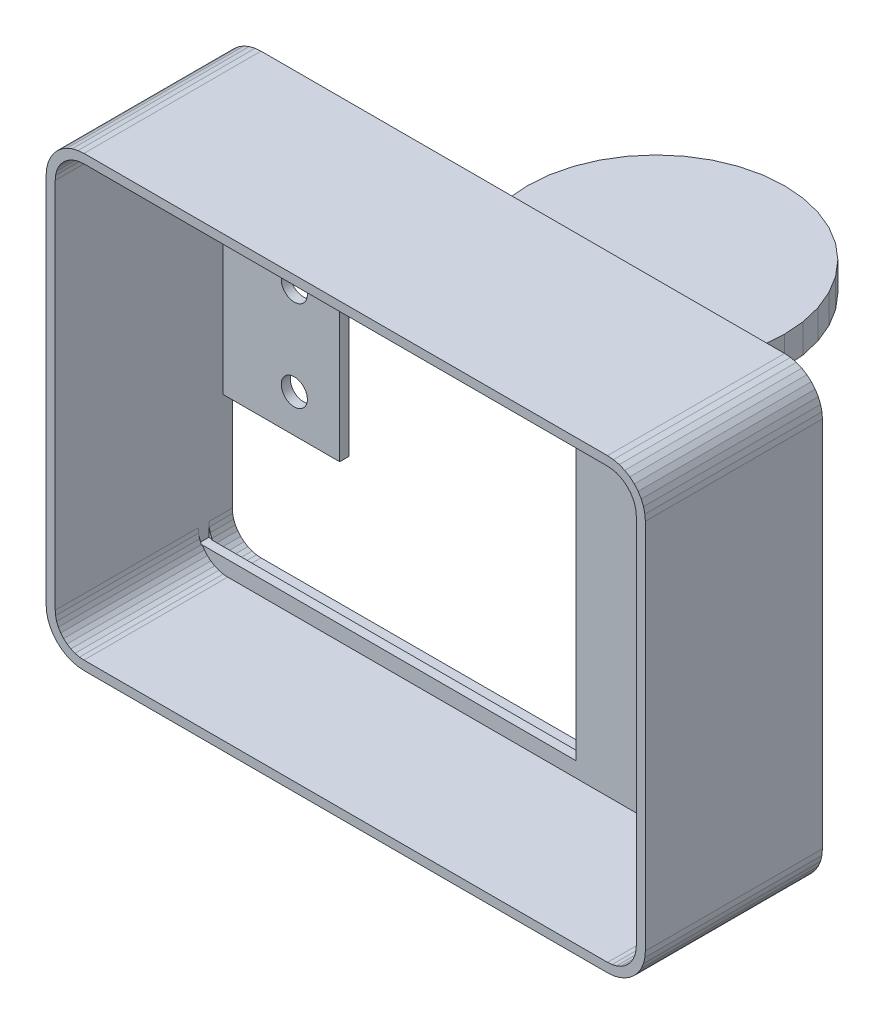
SolidWorks part; units mm, degrees
ref_plane "Front Plane" through (0, 0, 0) normal (0, 0, 1) x (1, 0, 0)
ref_plane "Top Plane" through (0, 0, 0) normal (0, 1, 0) x (1, 0, 0)
ref_plane "Right Plane" through (0, 0, 0) normal (1, 0, 0) x (0, 0, -1)
sketch "Sketch1" plane through (0, 0, 0) normal (0, 0, 1) x (1, 0, 0)
  line L0 (-41.6, -24.6) -> (-41.5384, -25.3822)
  line L1 (-41.5384, -25.3822) -> (-41.3553, -26.1451)
  line L2 (-41.3553, -26.1451) -> (-41.055, -26.87)
  line L3 (-41.055, -26.87) -> (-40.6451, -27.5389)
  line L4 (-40.6451, -27.5389) -> (-40.1355, -28.1355)
  line L5 (-40.1355, -28.1355) -> (-39.5389, -28.6451)
  line L6 (-39.5389, -28.6451) -> (-38.87, -29.055)
  line L7 (-38.87, -29.055) -> (-38.1451, -29.3553)
  line L8 (-38.1451, -29.3553) -> (-37.3822, -29.5384)
  line L9 (-37.3822, -29.5384) -> (-36.6, -29.6)
  line L10 (-36.6, -29.6) -> (32.6, -29.6)
  line L11 (32.6, -29.6) -> (33.3822, -29.5384)
  line L12 (33.3822, -29.5384) -> (34.1451, -29.3553)
  line L13 (34.1451, -29.3553) -> (34.87, -29.055)
  line L14 (34.87, -29.055) -> (35.5389, -28.6451)
  line L15 (35.5389, -28.6451) -> (36.1355, -28.1355)
  line L16 (36.1355, -28.1355) -> (36.6451, -27.5389)
  line L17 (36.6451, -27.5389) -> (37.055, -26.87)
  line L18 (37.055, -26.87) -> (37.3553, -26.1451)
  line L19 (37.3553, -26.1451) -> (37.5384, -25.3822)
  line L20 (37.5384, -25.3822) -> (37.6, -24.6)
  line L21 (37.6, -24.6) -> (37.6, 24.6)
  line L22 (37.6, 24.6) -> (37.5384, 25.3822)
  line L23 (37.5384, 25.3822) -> (37.3553, 26.1451)
  line L24 (37.3553, 26.1451) -> (37.055, 26.87)
  line L25 (37.055, 26.87) -> (36.6451, 27.5389)
  line L26 (36.6451, 27.5389) -> (36.1355, 28.1355)
  line L27 (36.1355, 28.1355) -> (35.5389, 28.6451)
  line L28 (35.5389, 28.6451) -> (34.87, 29.055)
  line L29 (34.87, 29.055) -> (34.1451, 29.3553)
  line L30 (34.1451, 29.3553) -> (33.3822, 29.5384)
  line L31 (33.3822, 29.5384) -> (32.6, 29.6)
  line L32 (32.6, 29.6) -> (-36.6, 29.6)
  line L33 (-36.6, 29.6) -> (-37.3822, 29.5384)
  line L34 (-37.3822, 29.5384) -> (-38.1451, 29.3553)
  line L35 (-38.1451, 29.3553) -> (-38.87, 29.055)
  line L36 (-38.87, 29.055) -> (-39.5389, 28.6451)
  line L37 (-39.5389, 28.6451) -> (-40.1355, 28.1355)
  line L38 (-40.1355, 28.1355) -> (-40.6451, 27.5389)
  line L39 (-40.6451, 27.5389) -> (-41.055, 26.87)
  line L40 (-41.055, 26.87) -> (-41.3553, 26.1451)
  line L41 (-41.3553, 26.1451) -> (-41.5384, 25.3822)
  line L42 (-41.5384, 25.3822) -> (-41.6, 24.6)
  line L43 (-41.6, 24.6) -> (-41.6, -24.6)
extrude "Boss-Extrude1" add sketch "Sketch1" along normal blind 23.4 from offset 23.4
sketch "Sketch2" plane through (0, 0, 0) normal (0, 0, 1) x (1, 0, 0)
  line L0 (-40.4, -24.6) -> (-40.3532, -25.1945)
  line L1 (-40.3532, -25.1945) -> (-40.214, -25.7743)
  line L2 (-40.214, -25.7743) -> (-39.9858, -26.3252)
  line L3 (-39.9858, -26.3252) -> (-39.6743, -26.8336)
  line L4 (-39.6743, -26.8336) -> (-39.287, -27.287)
  line L5 (-39.287, -27.287) -> (-38.8336, -27.6743)
  line L6 (-38.8336, -27.6743) -> (-38.3252, -27.9858)
  line L7 (-38.3252, -27.9858) -> (-37.7743, -28.214)
  line L8 (-37.7743, -28.214) -> (-37.1945, -28.3532)
  line L9 (-37.1945, -28.3532) -> (-36.6, -28.4)
  line L10 (-36.6, -28.4) -> (32.6, -28.4)
  line L11 (32.6, -28.4) -> (33.1945, -28.3532)
  line L12 (33.1945, -28.3532) -> (33.7743, -28.214)
  line L13 (33.7743, -28.214) -> (34.3252, -27.9858)
  line L14 (34.3252, -27.9858) -> (34.8336, -27.6743)
  line L15 (34.8336, -27.6743) -> (35.287, -27.287)
  line L16 (35.287, -27.287) -> (35.6743, -26.8336)
  line L17 (35.6743, -26.8336) -> (35.9858, -26.3252)
  line L18 (35.9858, -26.3252) -> (36.214, -25.7743)
  line L19 (36.214, -25.7743) -> (36.3532, -25.1945)
  line L20 (36.3532, -25.1945) -> (36.4, -24.6)
  line L21 (36.4, -24.6) -> (36.4, 24.6)
  line L22 (36.4, 24.6) -> (36.3532, 25.1945)
  line L23 (36.3532, 25.1945) -> (36.214, 25.7743)
  line L24 (36.214, 25.7743) -> (35.9858, 26.3252)
  line L25 (35.9858, 26.3252) -> (35.6743, 26.8336)
  line L26 (35.6743, 26.8336) -> (35.287, 27.287)
  line L27 (35.287, 27.287) -> (34.8336, 27.6743)
  line L28 (34.8336, 27.6743) -> (34.3252, 27.9858)
  line L29 (34.3252, 27.9858) -> (33.7743, 28.214)
  line L30 (33.7743, 28.214) -> (33.1945, 28.3532)
  line L31 (33.1945, 28.3532) -> (32.6, 28.4)
  line L32 (32.6, 28.4) -> (-36.6, 28.4)
  line L33 (-36.6, 28.4) -> (-37.1945, 28.3532)
  line L34 (-37.1945, 28.3532) -> (-37.7743, 28.214)
  line L35 (-37.7743, 28.214) -> (-38.3252, 27.9858)
  line L36 (-38.3252, 27.9858) -> (-38.8336, 27.6743)
  line L37 (-38.8336, 27.6743) -> (-39.287, 27.287)
  line L38 (-39.287, 27.287) -> (-39.6743, 26.8336)
  line L39 (-39.6743, 26.8336) -> (-39.9858, 26.3252)
  line L40 (-39.9858, 26.3252) -> (-40.214, 25.7743)
  line L41 (-40.214, 25.7743) -> (-40.3532, 25.1945)
  line L42 (-40.3532, 25.1945) -> (-40.4, 24.6)
  line L43 (-40.4, 24.6) -> (-40.4, -24.6)
extrude "Cut-Extrude1" cut sketch "Sketch2" against normal through all and the other way through all
sketch "Sketch3" plane through (0, 0, 0) normal (0, 0, 1) x (1, 0, 0)
  line L0 (-40.4, -24.6) -> (-40.3532, -25.1945)
  line L1 (-40.3532, -25.1945) -> (-40.214, -25.7743)
  line L2 (-40.214, -25.7743) -> (-39.9858, -26.3252)
  line L3 (-39.9858, -26.3252) -> (-39.6743, -26.8336)
  line L4 (-39.6743, -26.8336) -> (-39.287, -27.287)
  line L5 (-39.287, -27.287) -> (-38.8336, -27.6743)
  line L6 (-38.8336, -27.6743) -> (-38.3252, -27.9858)
  line L7 (-38.3252, -27.9858) -> (-37.7743, -28.214)
  line L8 (-37.7743, -28.214) -> (-37.1945, -28.3532)
  line L9 (-37.1945, -28.3532) -> (-36.6, -28.4)
  line L10 (-36.6, -28.4) -> (32.6, -28.4)
  line L11 (32.6, -28.4) -> (33.1945, -28.3532)
  line L12 (33.1945, -28.3532) -> (33.7743, -28.214)
  line L13 (33.7743, -28.214) -> (34.3252, -27.9858)
  line L14 (34.3252, -27.9858) -> (34.8336, -27.6743)
  line L15 (34.8336, -27.6743) -> (35.287, -27.287)
  line L16 (35.287, -27.287) -> (35.6743, -26.8336)
  line L17 (35.6743, -26.8336) -> (35.9858, -26.3252)
  line L18 (35.9858, -26.3252) -> (36.214, -25.7743)
  line L19 (36.214, -25.7743) -> (36.3532, -25.1945)
  line L20 (36.3532, -25.1945) -> (36.4, -24.6)
  line L21 (36.4, -24.6) -> (36.4, 24.6)
  line L22 (36.4, 24.6) -> (36.3532, 25.1945)
  line L23 (36.3532, 25.1945) -> (36.214, 25.7743)
  line L24 (36.214, 25.7743) -> (35.9858, 26.3252)
  line L25 (35.9858, 26.3252) -> (35.6743, 26.8336)
  line L26 (35.6743, 26.8336) -> (35.287, 27.287)
  line L27 (35.287, 27.287) -> (34.8336, 27.6743)
  line L28 (34.8336, 27.6743) -> (34.3252, 27.9858)
  line L29 (34.3252, 27.9858) -> (33.7743, 28.214)
  line L30 (33.7743, 28.214) -> (33.1945, 28.3532)
  line L31 (33.1945, 28.3532) -> (32.6, 28.4)
  line L32 (32.6, 28.4) -> (-36.6, 28.4)
  line L33 (-36.6, 28.4) -> (-37.1945, 28.3532)
  line L34 (-37.1945, 28.3532) -> (-37.7743, 28.214)
  line L35 (-37.7743, 28.214) -> (-38.3252, 27.9858)
  line L36 (-38.3252, 27.9858) -> (-38.8336, 27.6743)
  line L37 (-38.8336, 27.6743) -> (-39.287, 27.287)
  line L38 (-39.287, 27.287) -> (-39.6743, 26.8336)
  line L39 (-39.6743, 26.8336) -> (-39.9858, 26.3252)
  line L40 (-39.9858, 26.3252) -> (-40.214, 25.7743)
  line L41 (-40.214, 25.7743) -> (-40.3532, 25.1945)
  line L42 (-40.3532, 25.1945) -> (-40.4, 24.6)
  line L43 (-40.4, 24.6) -> (-40.4, -24.6)
extrude "Boss-Extrude2" add sketch "Sketch3" along normal blind 1.2 from offset 20.2
sketch "Sketch4" plane through (0, 0, 0) normal (0, 0, 1) x (1, 0, 0)
  line L0 (-40.4, -26.4) -> (9.4, -26.4)
  line L1 (9.4, -26.4) -> (9.4, 12.4)
  line L2 (9.4, 12.4) -> (-40.4, 12.4)
  line L3 (-40.4, 12.4) -> (-40.4, -26.4)
extrude "Cut-Extrude2" cut sketch "Sketch4" along normal blind 1.4 from offset 20.3
sketch "Sketch5" plane through (0, 0, 0) normal (0, 0, 1) x (1, 0, 0)
  line L0 (-40.4, -11) -> (-25, -11)
  line L1 (-25, -11) -> (-25, 11)
  line L2 (-25, 11) -> (-40.4, 11)
  line L3 (-40.4, 11) -> (-40.4, -11)
extrude "Boss-Extrude3" add sketch "Sketch5" along normal blind 1.2 from offset 23.4
sketch "Sketch6" plane through (0, 0, 0) normal (0, 0, 1) x (1, 0, 0)
  circle A0 centre (-31, 6) radius 1.725
  circle A1 centre (-31, -6) radius 1.725
extrude "Cut-Extrude3" cut sketch "Sketch6" against normal through all and the other way through all
sketch "Sketch7" plane through (0, 0, 0) normal (0, 1, 0) x (1, 0, 0)
  line L0 (-17, 39) -> (-16.7907, 41.6594)
  line L1 (-16.7907, 41.6594) -> (-16.168, 44.2533)
  line L2 (-16.168, 44.2533) -> (-15.1471, 46.7178)
  line L3 (-15.1471, 46.7178) -> (-13.7533, 48.9923)
  line L4 (-13.7533, 48.9923) -> (-12.0208, 51.0208)
  line L5 (-12.0208, 51.0208) -> (-9.9923, 52.7533)
  line L6 (-9.9923, 52.7533) -> (-7.7178, 54.1471)
  line L7 (-7.7178, 54.1471) -> (-5.2533, 55.168)
  line L8 (-5.2533, 55.168) -> (-2.6594, 55.7907)
  line L9 (-2.6594, 55.7907) -> (0, 56)
  line L10 (0, 56) -> (2.6594, 55.7907)
  line L11 (2.6594, 55.7907) -> (5.2533, 55.168)
  line L12 (5.2533, 55.168) -> (7.7178, 54.1471)
  line L13 (7.7178, 54.1471) -> (9.9923, 52.7533)
  line L14 (9.9923, 52.7533) -> (12.0208, 51.0208)
  line L15 (12.0208, 51.0208) -> (13.7533, 48.9923)
  line L16 (13.7533, 48.9923) -> (15.1471, 46.7178)
  line L17 (15.1471, 46.7178) -> (16.168, 44.2533)
  line L18 (16.168, 44.2533) -> (16.7907, 41.6594)
  line L19 (16.7907, 41.6594) -> (17, 39)
  line L20 (17, 39) -> (16.7907, 36.3406)
  line L21 (16.7907, 36.3406) -> (14.9754, 19.6871)
  line L22 (14.9754, 19.6871) -> (14.9021, 19.382)
  line L23 (14.9021, 19.382) -> (14.782, 19.092)
  line L24 (14.782, 19.092) -> (14.618, 18.8244)
  line L25 (14.618, 18.8244) -> (14.4142, 18.5858)
  line L26 (14.4142, 18.5858) -> (14.1756, 18.382)
  line L27 (14.1756, 18.382) -> (13.908, 18.218)
  line L28 (13.908, 18.218) -> (13.618, 18.0979)
  line L29 (13.618, 18.0979) -> (13.3129, 18.0246)
  line L30 (13.3129, 18.0246) -> (13, 18)
  line L31 (13, 18) -> (-13, 18)
  line L32 (-13, 18) -> (-13.3129, 18.0246)
  line L33 (-13.3129, 18.0246) -> (-13.618, 18.0979)
  line L34 (-13.618, 18.0979) -> (-13.908, 18.218)
  line L35 (-13.908, 18.218) -> (-14.1756, 18.382)
  line L36 (-14.1756, 18.382) -> (-14.4142, 18.5858)
  line L37 (-14.4142, 18.5858) -> (-14.618, 18.8244)
  line L38 (-14.618, 18.8244) -> (-14.782, 19.092)
  line L39 (-14.782, 19.092) -> (-14.9021, 19.382)
  line L40 (-14.9021, 19.382) -> (-14.9754, 19.6871)
  line L41 (-14.9754, 19.6871) -> (-16.7907, 36.3406)
  line L42 (-16.7907, 36.3406) -> (-17, 39)
extrude "Boss-Extrude4" add sketch "Sketch7" along normal blind 3.8 from offset 12.4
sketch "Sketch8" plane through (0, 0, 0) normal (0, 1, 0) x (1, 0, 0)
  line L0 (-15.8, 39) -> (-15.6055, 41.4717)
  line L1 (-15.6055, 41.4717) -> (-15.0267, 43.8825)
  line L2 (-15.0267, 43.8825) -> (-14.0779, 46.173)
  line L3 (-14.0779, 46.173) -> (-12.7825, 48.287)
  line L4 (-12.7825, 48.287) -> (-11.1723, 50.1723)
  line L5 (-11.1723, 50.1723) -> (-9.287, 51.7825)
  line L6 (-9.287, 51.7825) -> (-7.173, 53.0779)
  line L7 (-7.173, 53.0779) -> (-4.8825, 54.0267)
  line L8 (-4.8825, 54.0267) -> (-2.4717, 54.6055)
  line L9 (-2.4717, 54.6055) -> (0, 54.8)
  line L10 (0, 54.8) -> (2.4717, 54.6055)
  line L11 (2.4717, 54.6055) -> (4.8825, 54.0267)
  line L12 (4.8825, 54.0267) -> (7.173, 53.0779)
  line L13 (7.173, 53.0779) -> (9.287, 51.7825)
  line L14 (9.287, 51.7825) -> (11.1723, 50.1723)
  line L15 (11.1723, 50.1723) -> (12.7825, 48.287)
  line L16 (12.7825, 48.287) -> (14.0779, 46.173)
  line L17 (14.0779, 46.173) -> (15.0267, 43.8825)
  line L18 (15.0267, 43.8825) -> (15.6055, 41.4717)
  line L19 (15.6055, 41.4717) -> (15.8, 39)
  line L20 (15.8, 39) -> (15.6055, 36.5283)
  line L21 (15.6055, 36.5283) -> (13.7754, 18.6871)
  line L22 (13.7754, 18.6871) -> (13.7021, 18.382)
  line L23 (13.7021, 18.382) -> (13.582, 18.092)
  line L24 (13.582, 18.092) -> (13.418, 17.8244)
  line L25 (13.418, 17.8244) -> (13.2142, 17.5858)
  line L26 (13.2142, 17.5858) -> (12.9756, 17.382)
  line L27 (12.9756, 17.382) -> (12.708, 17.218)
  line L28 (12.708, 17.218) -> (12.418, 17.0979)
  line L29 (12.418, 17.0979) -> (12.1129, 17.0246)
  line L30 (12.1129, 17.0246) -> (11.8, 17)
  line L31 (11.8, 17) -> (-11.8, 17)
  line L32 (-11.8, 17) -> (-12.1129, 17.0246)
  line L33 (-12.1129, 17.0246) -> (-12.418, 17.0979)
  line L34 (-12.418, 17.0979) -> (-12.708, 17.218)
  line L35 (-12.708, 17.218) -> (-12.9756, 17.382)
  line L36 (-12.9756, 17.382) -> (-13.2142, 17.5858)
  line L37 (-13.2142, 17.5858) -> (-13.418, 17.8244)
  line L38 (-13.418, 17.8244) -> (-13.582, 18.092)
  line L39 (-13.582, 18.092) -> (-13.7021, 18.382)
  line L40 (-13.7021, 18.382) -> (-13.7754, 18.6871)
  line L41 (-13.7754, 18.6871) -> (-15.6055, 36.5283)
  line L42 (-15.6055, 36.5283) -> (-15.8, 39)
extrude "Cut-Extrude4" cut sketch "Sketch8" against normal mid plane 2.7 from offset 13.65
